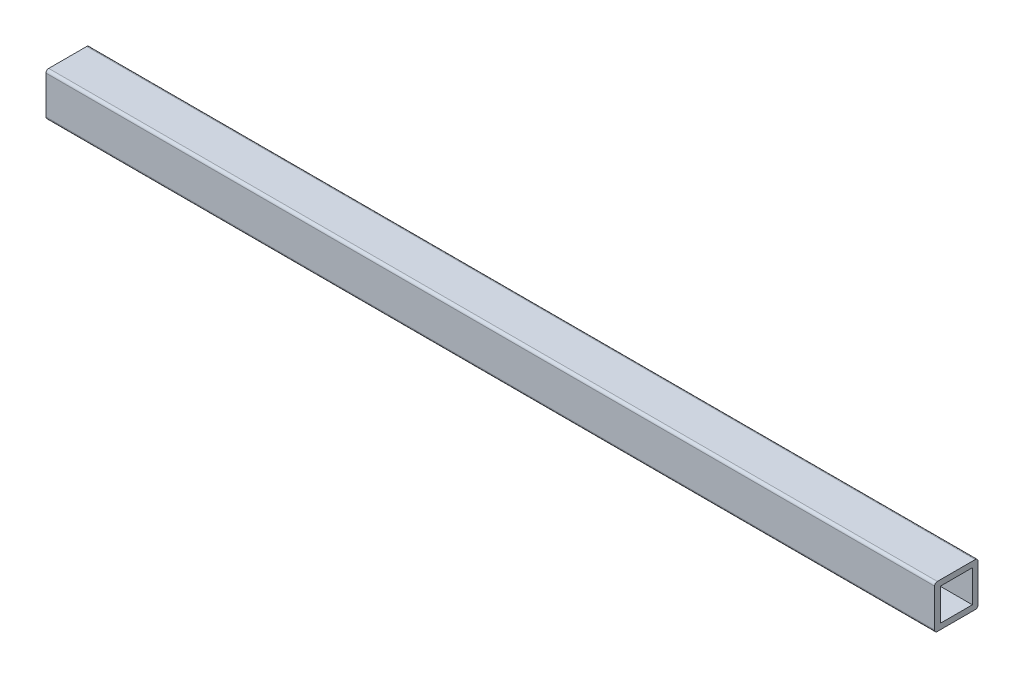
SolidWorks part; units mm, degrees
ref_plane "Front Plane" through (0, 0, 0) normal (0, 0, 1) x (1, 0, 0)
ref_plane "Top Plane" through (0, 0, 0) normal (0, 1, 0) x (1, 0, 0)
ref_plane "Right Plane" through (0, 0, 0) normal (1, 0, 0) x (0, 0, -1)
sketch "Sketch1" plane through (0, 0, 0) normal (0, 0, 1) x (1, 0, 0)
  line L0 (0, 0) -> (260.096, 0)
  dimension "D1" = 260.096
other "Structural Member1"
ref_plane "Plane1" through (0, 0, 0) normal (1, 0, 0) x (0, 1, 0)
sketch "Sketch11" plane through (0, 0, 0) normal (1, 0, 0) x (0, 1, 0)
  line L0 (-6.35, -6.35) -> (6.35, 6.35) construction
  line L1 (-5.5562, 6.35) -> (5.5562, 6.35)
  line L2 (-6.35, 5.5562) -> (-6.35, -5.5562)
  line L3 (-5.5562, -6.35) -> (5.5562, -6.35)
  line L4 (6.35, 5.5562) -> (6.35, -5.5562)
  line L5 (-4.699, 4.699) -> (-4.699, -4.699)
  line L6 (-4.699, -4.699) -> (4.699, -4.699)
  line L7 (4.699, 4.699) -> (4.699, -4.699)
  line L8 (-4.699, 4.699) -> (4.699, 4.699)
  line L9 (0, 0) -> (6.35, -6.35) construction
  line L10 (6.35, -6.35) -> (-6.35, 6.35) construction
  arc A0 (-6.35, -5.5562) -> (-5.5562, -6.35) centre (-5.5562, -5.5562) ccw
  arc A1 (5.5562, -6.35) -> (6.35, -5.5562) centre (5.5563, -5.5562) ccw
  arc A2 (5.5562, 6.35) -> (6.35, 5.5562) centre (5.5563, 5.5563) cw
  arc A3 (-5.5562, 6.35) -> (-6.35, 5.5562) centre (-5.5562, 5.5563) ccw
  arc A4 (-4.699, -4.699) -> (-4.699, -4.699) centre (-4.699, -4.699) ccw
  arc A5 (4.699, -4.699) -> (4.699, -4.699) centre (4.699, -4.699) ccw
  arc A6 (4.699, 4.699) -> (4.699, 4.699) centre (4.699, 4.699) cw
  arc A7 (-4.699, 4.699) -> (-4.699, 4.699) centre (-4.699, 4.699) ccw
  point P11 (6.35, -6.35)
  point P17 (-6.35, 6.35)
  point P18 (-6.35, 0.5988)
  point P19 (0, 6.35)
  point P20 (6.35, 0)
  point P21 (0, -6.35)
  point P35 (0, 0)
  dimension "D3" = 0.7937
  dimension "D1" = 12.7
  dimension "D2" = 12.7
  dimension "D4" = 1.651
